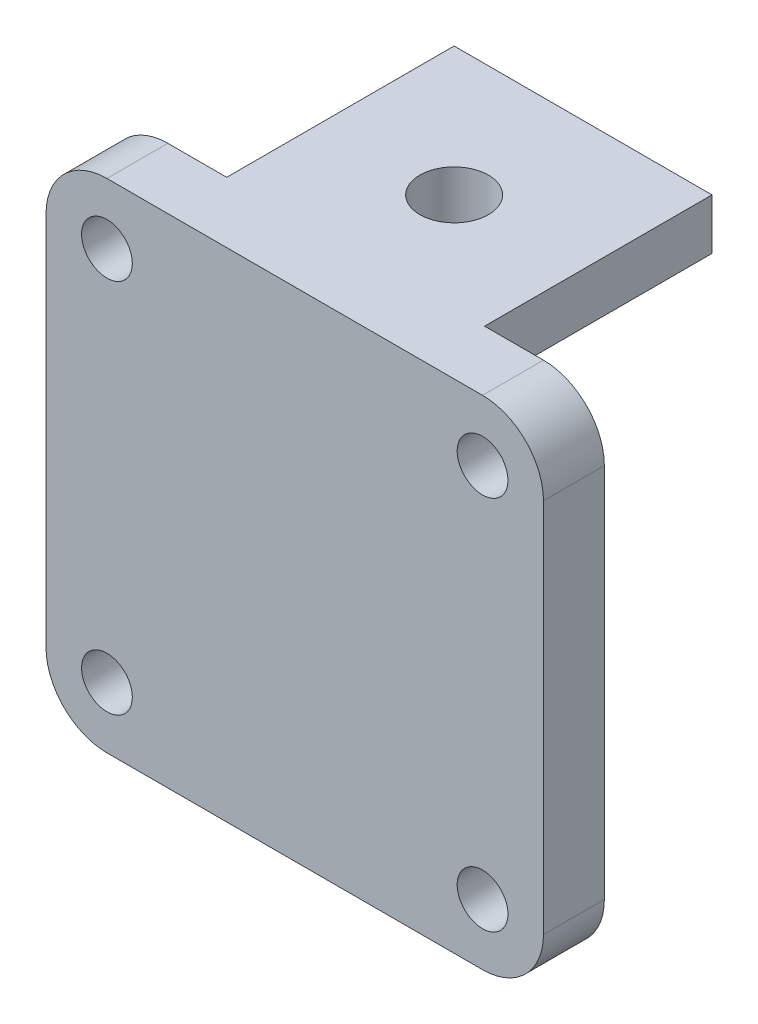
SolidWorks part; units mm, degrees
ref_plane "Front Plane" through (0, 0, 0) normal (0, 0, 1) x (1, 0, 0)
ref_plane "Top Plane" through (0, 0, 0) normal (0, 1, 0) x (1, 0, 0)
ref_plane "Right Plane" through (0, 0, 0) normal (1, 0, 0) x (0, 0, -1)
sketch "Sketch1" plane through (0, 0, 0) normal (0, 1, 0) x (1, 0, 0)
  line L1 (-12.7, 12.7) -> (12.7, 12.7)
  line L2 (-12.7, 12.7) -> (-12.7, -12.7)
  line L3 (-12.7, -12.7) -> (12.7, -12.7)
  line L4 (12.7, 12.7) -> (12.7, -12.7)
  line L5 (-12.7, 12.7) -> (12.7, -12.7) construction
  line L6 (-12.7, -12.7) -> (12.7, 12.7) construction
  point P0 (0, 0)
  dimension "D1" = 25.4
  dimension "D2" = 25.4
extrude "Boss-Extrude1" add sketch "Sketch1" along normal blind 5
hole_wizard "1/4 Clearance Hole1" positions "Sketch2" profile "Sketch3" hole size "1/4" standard "ANSI Inch" end condition through all
sketch "Sketch2" plane through (0, 5, 0) normal (0, 1, 0) x (1, 0, 0)
  point P0 (0, 0)
sketch "Sketch3" plane through (0, 5, 0) normal (1, 0, 0) x (0, 0, 1)
  line L0 (0, 0) -> (0, 5)
  line L1 (0, 5) -> (3.3782, 5)
  line L2 (3.3782, 5) -> (3.3782, 0)
  line L5 (3.3782, 0) -> (0, 0)
  line L11 (0, -6.35) -> (0, 107.95) construction
  dimension "Thru Hole Dia." = 6.7564
  dimension "Thru Hole Depth" = 5
sketch "Sketch4" plane through (0, 0, 12.7) normal (0, 0, 1) x (1, 0, 0)
  line L0 (-24.5, -44) -> (-24.5, 5)
  line L1 (-18.5, -38) -> (18.5, -38) construction
  line L2 (-18.5, -38) -> (-18.5, -1) construction
  line L3 (-18.5, -1) -> (18.5, -1) construction
  line L4 (18.5, -38) -> (18.5, -1) construction
  line L5 (-18.5, -38) -> (18.5, -1) construction
  line L6 (-18.5, -1) -> (18.5, -38) construction
  line L7 (-24.5, 5) -> (24.5, 5)
  line L8 (24.5, -44) -> (24.5, 5)
  line L9 (-24.5, -44) -> (24.5, -44)
  line L10 (-12.7, 5) -> (12.7, 5) construction
  circle A0 centre (-18.5, -1) radius 2.5
  circle A1 centre (18.5, -1) radius 2.5
  circle A2 centre (18.5, -38) radius 2.5
  circle A3 centre (-18.5, -38) radius 2.5
  point P0 (0, -19.5)
  line M9 (-12.7, 0) -> (12.7, 0)
  line M10 (12.7, 0) -> (12.7, 5)
  line M11 (12.7, 5) -> (-12.7, 5)
  line M12 (-12.7, 5) -> (-12.7, 0)
  dimension "D4" = 5
  dimension "D1" = 6
  dimension "D2" = 37
  dimension "D3" = 37
extrude "Boss-Extrude2" add sketch "Sketch4" against normal mid plane 6 contours L0 L9 L8 L7 A3 A2 A1 A0 M10 M9 M12 | M12 M9 M10 M11
fillet "Fillet1" radius 6 4 edges at (24.5, -44, 12.7) (-24.5, -44, 12.7) (24.5, 5, 12.7) (-24.5, 5, 12.7)
